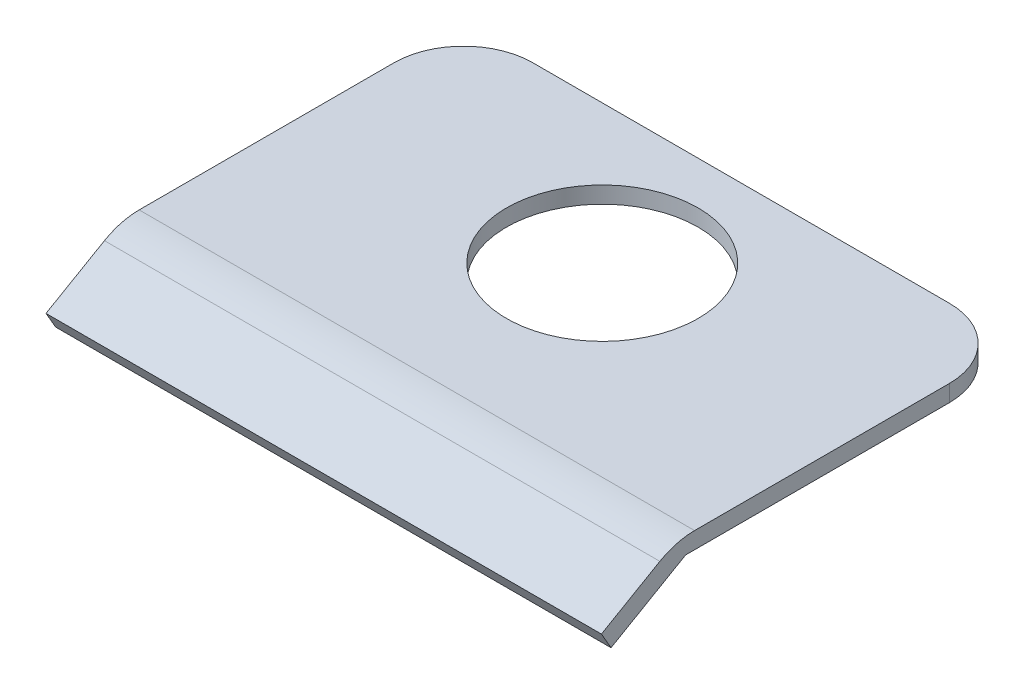
SolidWorks part; units mm, degrees
ref_plane "Front Plane" through (0, 0, 0) normal (0, 0, 1) x (1, 0, 0)
ref_plane "Top Plane" through (0, 0, 0) normal (0, 1, 0) x (1, 0, 0)
ref_plane "Right Plane" through (0, 0, 0) normal (1, 0, 0) x (0, 0, -1)
sketch "Sketch1" plane through (0, 0, 0) normal (0, 1, 0) x (1, 0, 0)
  line L0 (0, -1000) -> (0, 49000) construction
  line L1 (-25.4, 15.24) -> (25.4, 15.24)
  line L2 (-25.4, 15.24) -> (-25.4, -15.24)
  line L3 (-25.4, -15.24) -> (25.4, -15.24)
  line L4 (25.4, 15.24) -> (25.4, -15.24)
  line L5 (-25.4, 15.24) -> (25.4, -15.24) construction
  line L6 (-25.4, -15.24) -> (25.4, 15.24) construction
  circle A0 centre (0, 2.54) radius 8.763
  point P0 (0, 0)
  point P8 (3.5229, 5.8095)
  dimension "D3" = 17.526
  dimension "D1" = 50.8
  dimension "D2" = 30.48
  dimension "D4" = 12.7
extrude "Boss-Extrude1" add sketch "Sketch1" along normal blind 1.524
sketch "Sketch2" plane through (-25.4, 0, 0) normal (-1, 0, 0) x (0, 0, 1)
  line L0 (15.24, 0) -> (16.1199, 1.524) construction
  line L1 (15.24, 0) -> (22.0591, -3.937)
  line L2 (16.1199, 1.524) -> (22.939, -2.413)
  line L3 (22.0591, -3.937) -> (22.939, -2.413)
  line L4 (19.5294, -0.4445) -> (18.6495, -1.9685) construction
  line L5 (15.6799, 0.762) -> (22.499, -3.175) construction
  line L6 (-15.24, 1.524) -> (15.24, 1.524) construction
  line L7 (15.24, 1.524) -> (16.1199, 1.524)
  line L8 (15.24, 1.524) -> (15.24, 0) construction
  line L9 (15.24, 1.524) -> (15.24, 0)
  point P7 (22.8165, -2.8164)
  point P114 (19.0895, -1.2065)
  dimension "D1" = 7.874
  dimension "D2" = 30
extrude "Boss-Extrude2" add sketch "Sketch2" against normal up to surface (50.8 mm away) up to face at (25.4, 0.762, 0)
fillet "Fillet1" radius 6.35 3 edges at (-25.4, 0.762, -15.24) (25.4, 0.762, -15.24) (0, 1.524, 16.1199)
